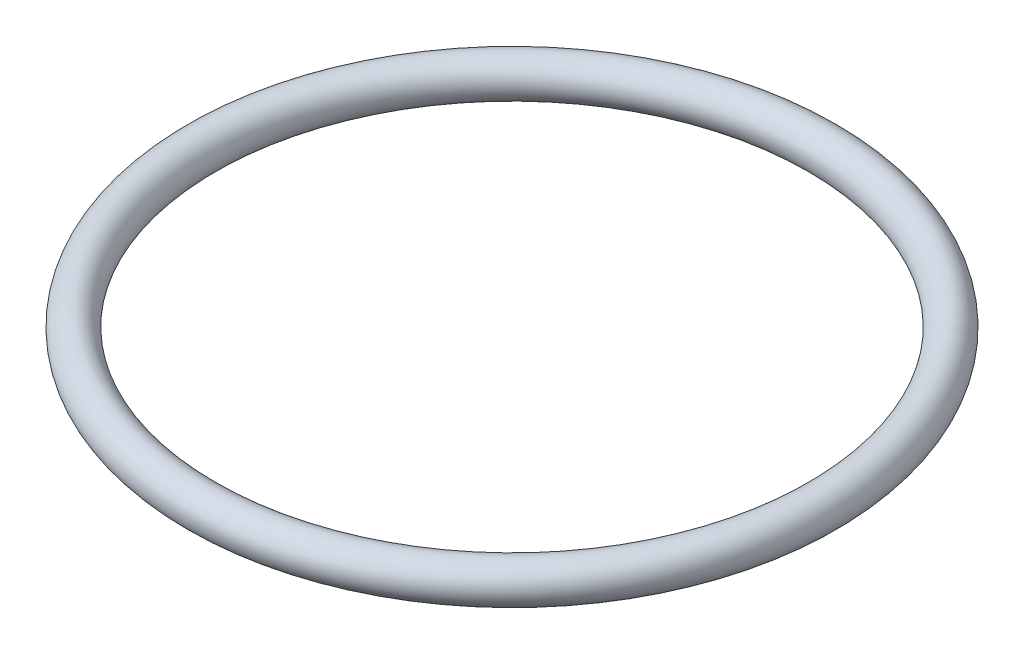
SolidWorks part; units mm, degrees
ref_plane "Front Plane" through (0, 0, 0) normal (0, 0, 1) x (1, 0, 0)
ref_plane "Top Plane" through (0, 0, 0) normal (0, 1, 0) x (1, 0, 0)
ref_plane "Right Plane" through (0, 0, 0) normal (1, 0, 0) x (0, 0, -1)
sketch "Sketch1" plane through (0, 0, 0) normal (1, 0, 0) x (0, 0, -1)
  line L0 (0, 6.3378) -> (0, -4.1069) construction
  circle A0 centre (-8, 0) radius 0.5
  dimension "D1" = 1
  dimension "D2" = 16
revolve "Revolve1" add sketch "Sketch1" angle 360 about L0
